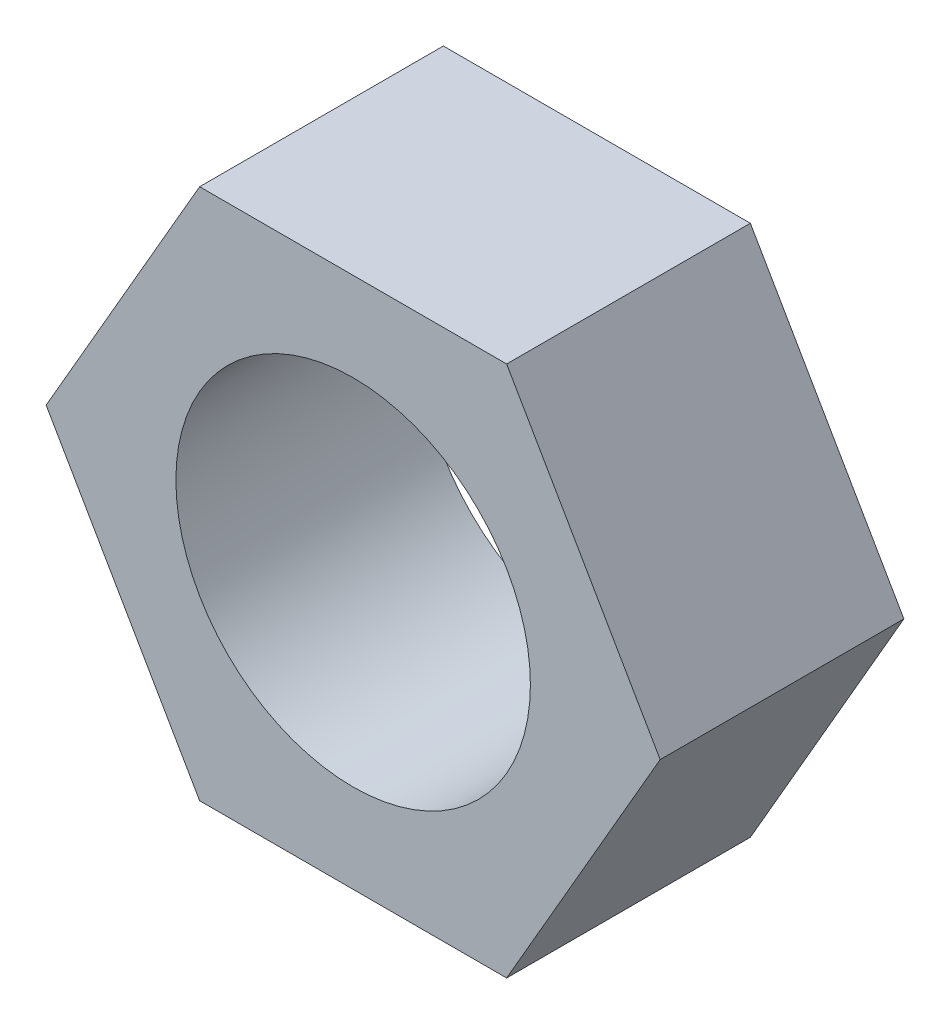
SolidWorks part; units mm, degrees
ref_plane "Front Plane" through (0, 0, 0) normal (0, 0, 1) x (1, 0, 0)
ref_plane "Top Plane" through (0, 0, 0) normal (0, 1, 0) x (1, 0, 0)
ref_plane "Right Plane" through (0, 0, 0) normal (1, 0, 0) x (0, 0, -1)
sketch "Sketch2" plane through (0, 0, 0) normal (0, 0, 1) x (1, 0, 0)
  line L1 (-6.9282, 0) -> (-3.4641, -6)
  line L2 (-3.4641, -6) -> (3.4641, -6)
  line L3 (3.4641, -6) -> (6.9282, 0)
  line L4 (6.9282, 0) -> (3.4641, 6)
  line L5 (3.4641, 6) -> (-3.4641, 6)
  line L6 (-3.4641, 6) -> (-6.9282, 0)
  circle A0 centre (0, 0) radius 6 construction
  circle A1 centre (0, 0) radius 4
  dimension "D2" = 8
  dimension "D1" = 12
extrude "Boss-Extrude1" add sketch "Sketch2" along normal blind 5.5
